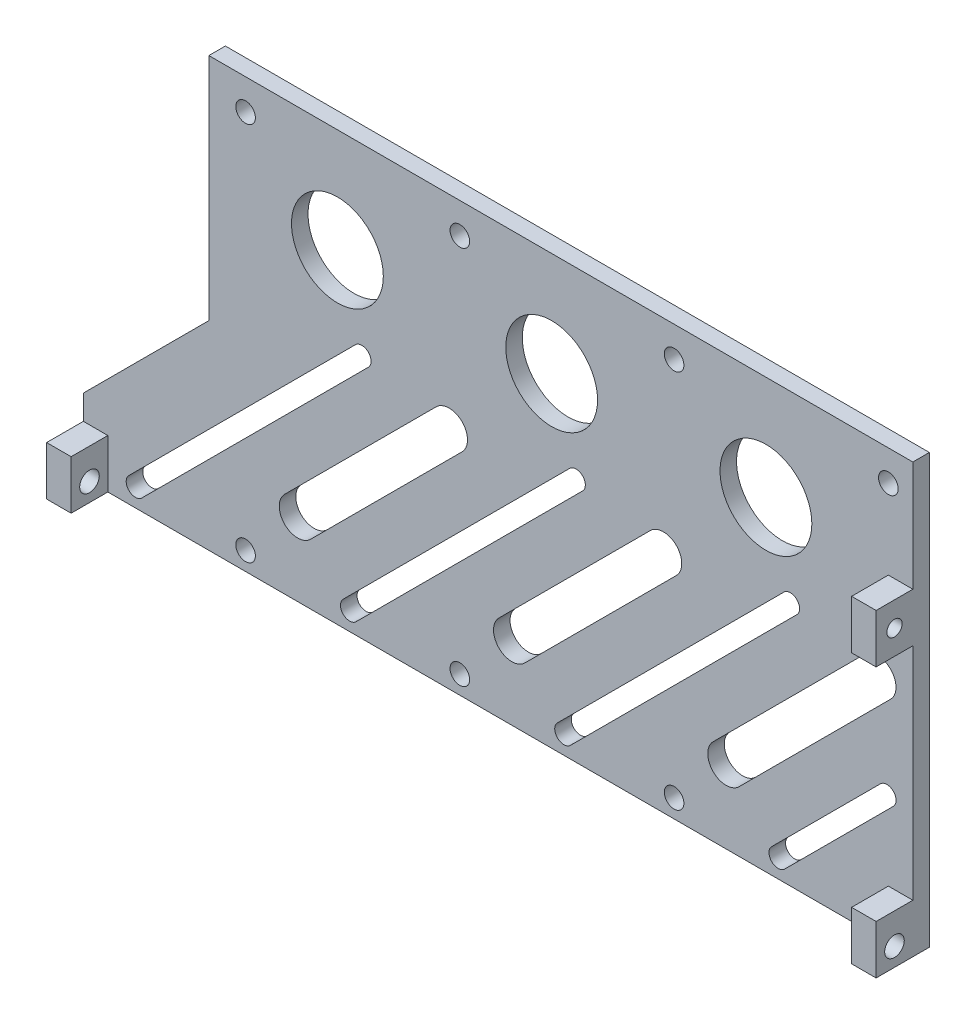
SolidWorks part; units mm, degrees
ref_plane "前视基准面" through (0, 0, 0) normal (0, 0, 1) x (1, 0, 0)
ref_plane "上视基准面" through (0, 0, 0) normal (0, 1, 0) x (1, 0, 0)
ref_plane "右视基准面" through (0, 0, 0) normal (1, 0, 0) x (0, 0, -1)
sketch "草图1" plane through (0, 0, 0) normal (0, 0, 1) x (1, 0, 0)
  line L1 (-142.5, 35) -> (142.5, 35)
  line L2 (-142.5, 35) -> (-142.5, -35)
  line L3 (-142.5, -35) -> (142.5, -35)
  line L4 (142.5, 35) -> (142.5, -35)
  line L5 (-142.5, 35) -> (142.5, -35) construction
  line L6 (-142.5, -35) -> (142.5, 35) construction
  point P0 (0, 0)
  dimension "D1" = 285
  dimension "D2" = 70
extrude "凸台-拉伸1" add sketch "草图1" along normal blind 2.7
sketch "草图2" plane through (0, 0, 2.7) normal (0, 0, 1) x (1, 0, 0)
  line L1 (0, -32) -> (0, 35) construction
  line L2 (142.5, 35) -> (-142.5, 35) construction
  line L3 (-142.5, 35) -> (-142.5, -35) construction
  line L4 (-124.5, -32) -> (-87.5, 5) construction
  line L5 (-125.5607, -30.9393) -> (-88.5607, 6.0607)
  line L6 (-123.4393, -33.0607) -> (-86.4393, 3.9393)
  line L7 (-142.5, -35) -> (142.5, -35) construction
  arc A1 (-125.5607, -30.9393) -> (-123.4393, -33.0607) centre (-124.5, -32) ccw
  arc A2 (-86.4393, 3.9393) -> (-88.5607, 6.0607) centre (-87.5, 5) ccw
  circle A4 centre (-106.5, -32) radius 1.6
  circle A6 centre (-106.5, 30) radius 1.6
  circle A10 centre (-126.5, 18) radius 7.5
  point P4 (-106, -13.5)
  dimension "D6" = 3.2
  dimension "D7" = 3.2
  dimension "D17" = 15
  dimension "D2" = 3
  dimension "D3" = 45
  dimension "D4" = 3
  dimension "D5" = 40
  dimension "D8" = 65
  dimension "D9" = 18
  dimension "D10" = 18
  dimension "D18" = 20
  dimension "D19" = 53
extrude "切除-拉伸1" cut sketch "草图2" against normal through all
pattern_linear "阵列(线性)1" count 8 spacing 35 along (1, 0, 0) of "切除-拉伸1"
sketch "草图5" plane through (0, 0, 2.7) normal (0, 0, 1) x (1, 0, 0)
  line L0 (-142.5, -35) -> (142.5, -35) construction
  line L1 (-142.5, -35) -> (-138.5, -35)
  line L2 (-142.5, -35) -> (-142.5, -27)
  line L3 (-142.5, -27) -> (-138.5, -27)
  line L4 (-138.5, -35) -> (-138.5, -27)
  line L5 (142.5, -35) -> (138.5, -35)
  line L6 (142.5, -35) -> (142.5, -27)
  line L7 (142.5, -27) -> (138.5, -27)
  line L8 (138.5, -35) -> (138.5, -27)
  line L9 (3, -35) -> (11, -35)
  line L10 (3, -35) -> (3, -27)
  line L11 (3, -27) -> (11, -27)
  line L12 (11, -35) -> (11, -27)
  line L13 (-1.5, -32) -> (15.5, -32) construction
  line L14 (7, -32) -> (7, -27) construction
  line L15 (-142.5, 35) -> (-142.5, -35) construction
  line L16 (142.5, -35) -> (142.5, -12.1213) construction
  line L17 (-142.5, 17) -> (-138.5, 17)
  line L18 (-142.5, 17) -> (-142.5, 9)
  line L19 (-142.5, 9) -> (-138.5, 9)
  line L20 (-138.5, 17) -> (-138.5, 9)
  line L21 (142.5, 17) -> (138.5, 17)
  line L22 (142.5, 17) -> (142.5, 9)
  line L23 (142.5, 9) -> (138.5, 9)
  line L24 (138.5, 17) -> (138.5, 9)
  line L25 (-142.5, 13) -> (-138.5, 13) construction
  line L26 (-87.5, 5) -> (-52.5, 5) construction
  line L28 (-6, 17) -> (-2, 17)
  line L29 (-6, 17) -> (-6, 9)
  line L30 (-6, 9) -> (-2, 9)
  line L31 (-2, 17) -> (-2, 9)
  line L32 (-4, 18) -> (-4, 17) construction
  line L33 (-21.5, 18) -> (13.5, 18) construction
  point P44 (0, 0)
  point P45 (-4, 18)
  dimension "D1" = 8
  dimension "D2" = 8
  dimension "4" = 4
  dimension "D3" = 8
extrude "凸台-拉伸3" add sketch "草图5" along normal blind 6
sketch "草图7" plane through (-138.5, 0, 0) normal (1, 0, 0) x (0, 0, -1)
  line L0 (-8.7, -35) -> (-2.7, -35) construction
  line L1 (-5.7, -32) -> (-5.7, -35) construction
  line L2 (-8.7, 13) -> (-5.7, 13) construction
  line L3 (-8.7, 9) -> (-8.7, 17) construction
  circle A0 centre (-5.7, -32) radius 1.6
  circle A1 centre (-5.7, 13) radius 1.25
  point P8 (0, 0)
  dimension "D2" = 3.2
  dimension "D3" = 2.5
  dimension "D1" = 3
extrude "切除-拉伸3" cut sketch "草图7" against normal through all both and the other way through all
sketch "草图9" plane through (0, 0, 2.7) normal (0, 0, 1) x (1, 0, 0)
  line L0 (120.5, -32) -> (146.8842, -5.6158) construction
  line L2 (142.5, -7.8787) -> (119.4393, -30.9393) construction
  line L3 (137.1967, -13.182) -> (142.5, -7.8787)
  line L4 (142.5, -12.1213) -> (139.318, -15.3033)
  line L6 (142.5, -7.8787) -> (142.5, -12.1213)
  line L7 (11, -35) -> (138.5, -35) construction
  arc A1 (139.318, -15.3033) -> (137.1967, -13.182) centre (138.2574, -14.2426) ccw
  circle A2 centre (138.5, -32) radius 3
  dimension "D1" = 4.5
extrude "凸台-拉伸4" add sketch "草图9" against normal up to surface (2.7 mm away) up to face at (34, -13.5, 0)
sketch "草图10" plane through (0, 0, 2.7) normal (0, 0, 1) x (1, 0, 0)
  line L0 (-98, -23) -> (-73.2513, 1.7487) construction
  line L1 (-100.1213, -20.8787) -> (-75.3726, 3.8701)
  line L2 (-95.8787, -25.1213) -> (-71.1299, -0.3726)
  line L3 (-123.4393, -33.0607) -> (-86.4393, 3.9393) construction
  line L4 (-53.5607, 6.0607) -> (-90.5607, -30.9393) construction
  line L5 (-138.5, -35) -> (3, -35) construction
  arc A0 (-100.1213, -20.8787) -> (-95.8787, -25.1213) centre (-98, -23) ccw
  arc A1 (-71.1299, -0.3726) -> (-75.3726, 3.8701) centre (-73.2513, 1.7487) ccw
  point P2 (-85.6256, -10.6256)
  dimension "D1" = 6
  dimension "D2" = 12
  dimension "D3" = 35
extrude "切除-拉伸4" cut sketch "草图10" against normal through all
pattern_linear "阵列(线性)2" count 7 spacing 35 along (1, 0, 0) skipping (3, 0) of "切除-拉伸4"
pattern_linear "阵列(线性)3" count 2 spacing 35 along (-1, 0, 0) of "切除-拉伸4"
sketch "草图3" plane through (0, 0, 2.7) normal (0, 0, 1) x (1, 0, 0)
  line L1 (27.5, 35) -> (-142.5, 35)
  line L4 (27.5, 35) -> (27.5, -2.5)
  line L5 (13.5, 18) -> (48.5, 18) construction
  line L7 (27.5, -2.5) -> (7, -23)
  line L16 (-142.5, 35) -> (-142.5, -35)
  line L18 (7, -35) -> (7, -23)
  line L24 (11, -27) -> (3, -27) construction
  line L25 (-142.5, -35) -> (7, -35)
  line L26 (33.5, 30) -> (33.5, 21.3105) construction
  line L32 (-18.4393, -33.0607) -> (18.5607, 3.9393) construction
  line L33 (51.4393, 6.0607) -> (14.4393, -30.9393) construction
  line L34 (11.3846, -3.2367) -> (26.7633, -18.6154) construction
  circle A0 centre (13.5, 18) radius 7.5 construction
  circle A1 centre (48.5, 18) radius 7.5 construction
  point P11 (7, -27)
  point P13 (33.5, 21.3105)
  point P17 (19.0739, -10.9261)
  point P22 (33.3554, 22.5476)
  point P26 (40.4769, 40.1818)
  dimension "D1" = 6
extrude "切除-拉伸2" cut sketch "草图3" against normal through all both and the other way through all
